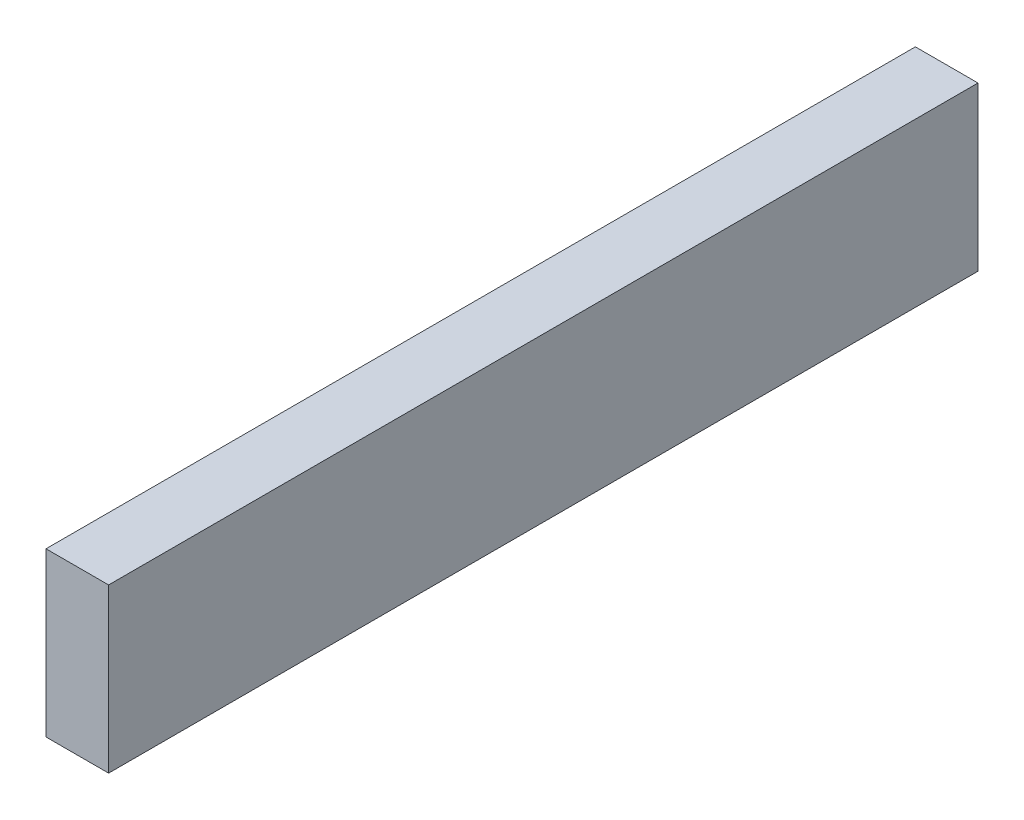
SolidWorks part; units mm, degrees
ref_plane "Front Plane" through (0, 0, 0) normal (0, 0, 1) x (1, 0, 0)
ref_plane "Top Plane" through (0, 0, 0) normal (0, 1, 0) x (1, 0, 0)
ref_plane "Right Plane" through (0, 0, 0) normal (1, 0, 0) x (0, 0, -1)
sketch "Sketch1" plane through (0, 0, 0) normal (0, 0, 1) x (1, 0, 0)
  line L1 (-7.3182, -19.05) -> (7.3182, -19.05)
  line L2 (-7.3182, -19.05) -> (-7.3182, 19.05)
  line L3 (-7.3182, 19.05) -> (7.3182, 19.05)
  line L4 (7.3182, -19.05) -> (7.3182, 19.05)
  line L5 (-7.3182, -19.05) -> (7.3182, 19.05) construction
  line L6 (-7.3182, 19.05) -> (7.3182, -19.05) construction
  point P0 (0, 0)
  dimension "D1" = 38.1
extrude "Boss-Extrude1" add sketch "Sketch1" along normal blind 203.2
